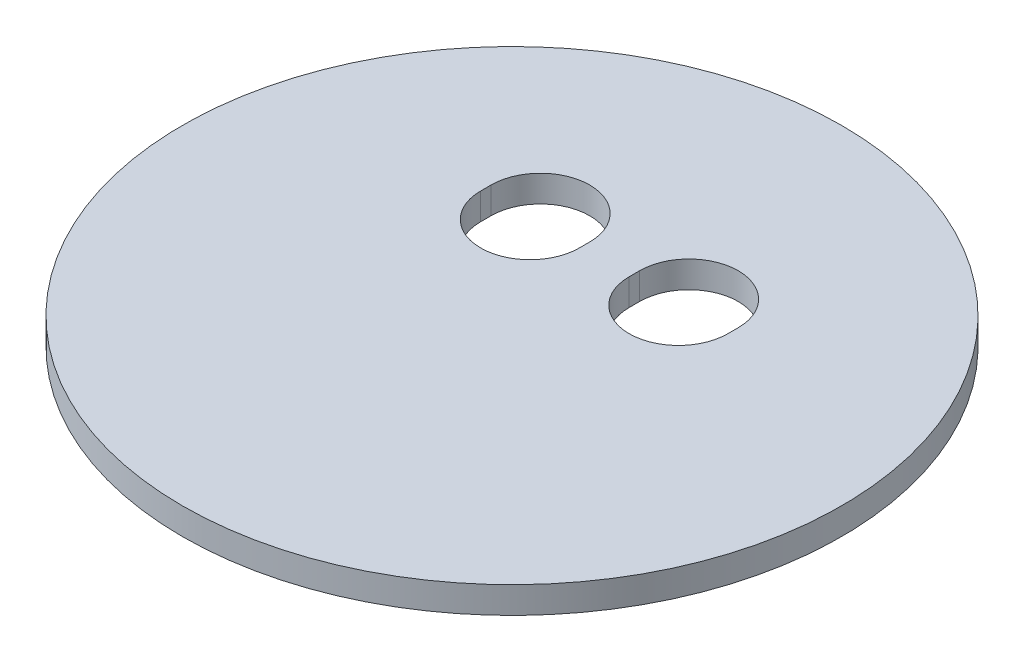
SolidWorks part; units mm, degrees
ref_plane "Front Plane" through (0, 0, 0) normal (0, 0, 1) x (1, 0, 0)
ref_plane "Top Plane" through (0, 0, 0) normal (0, 1, 0) x (1, 0, 0)
ref_plane "Right Plane" through (0, 0, 0) normal (1, 0, 0) x (0, 0, -1)
sketch "Sketch1" plane through (0, 0, 0) normal (0, 1, 0) x (1, 0, 0)
  circle A0 centre (0, 0) radius 12.36
  dimension "D1" = 24.72
extrude "Boss-Extrude1" add sketch "Sketch1" along normal blind 1
sketch "Sketch2" plane through (0, 1, 0) normal (0, 1, 0) x (1, 0, 0)
  line L0 (-2.785, 3.85) -> (-2.785, 3.46) construction
  line L1 (2.785, 3.85) -> (2.785, 3.46) construction
  line L2 (4.635, 3.85) -> (4.635, 3.46)
  line L3 (0.935, 3.85) -> (0.935, 3.46)
  line L4 (-0.935, 3.85) -> (-0.935, 3.46)
  line L5 (-4.635, 3.85) -> (-4.635, 3.46)
  line L6 (-2.785, 5.7) -> (2.785, 5.7) construction
  arc A3 (4.635, 3.85) -> (0.935, 3.85) centre (2.785, 3.85) ccw
  arc A4 (0.935, 3.46) -> (4.635, 3.46) centre (2.785, 3.46) ccw
  arc A5 (-0.935, 3.85) -> (-4.635, 3.85) centre (-2.785, 3.85) ccw
  arc A6 (-4.635, 3.46) -> (-0.935, 3.46) centre (-2.785, 3.46) ccw
  circle A7 centre (0, 0) radius 12.36 construction
  point P1 (-2.785, 3.655)
  point P2 (-4.635, 3.655)
  point P3 (-0.935, 3.655)
  point P8 (2.785, 3.655)
  point P14 (2.785, 5.7)
  point P15 (2.785, 1.61)
  point P16 (4.635, 3.655)
  point P17 (0.935, 3.655)
  point P20 (-2.785, 5.7)
  point P24 (-2.785, 1.61)
  point P29 (0, 5.7)
  dimension "D2" = 4.09
  dimension "D1" = 3.7
  dimension "D3" = 3.7
  dimension "D4" = 4.09
  dimension "D5" = 5.7
  dimension "D6" = 5.57
extrude "Cut-Extrude1" cut sketch "Sketch2" against normal through all
